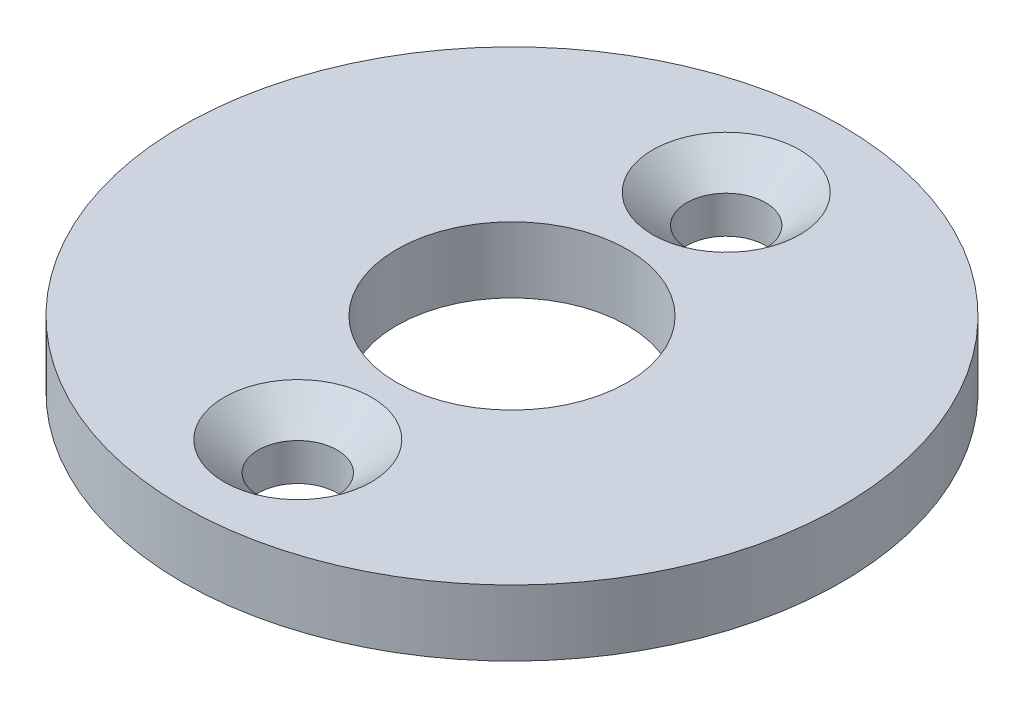
SolidWorks part; units mm, degrees
material "6061-T6 (SS)"
ref_plane "Front Plane" through (0, 0, 0) normal (0, 0, 1) x (1, 0, 0)
ref_plane "Top Plane" through (0, 0, 0) normal (0, 1, 0) x (1, 0, 0)
ref_plane "Right Plane" through (0, 0, 0) normal (1, 0, 0) x (0, 0, -1)
sketch "Sketch1" plane through (0, 0, 0) normal (0, 1, 0) x (1, 0, 0)
  circle A0 centre (0, 0) radius 5.5562
  circle A1 centre (0, 0) radius 15.875
  point P4 (0, 0)
  dimension "D1" = 11.1125
  dimension "D2" = 31.75
extrude "Boss-Extrude1" add sketch "Sketch1" along normal blind 3.175
hole_wizard "CSK for #6 Flat Head Machine Screw (100)1" positions "Sketch4" profile "Sketch2" countersink size "#6" standard "ANSI Inch" end condition through all
sketch "Sketch4" plane through (0, 3.175, 0) normal (0, 1, 0) x (1, 0, 0)
  circle A0 centre (0, 0) radius 10.3187 construction
  point P0 (0, -10.3187)
  point P2 (0, 10.3187)
  dimension "D1" = 20.6375
sketch "Sketch2" plane through (0, 3.175, 10.3187) normal (1, 0, 0) x (0, 0, 1)
  line L0 (0, 0) -> (0, 3.175)
  line L1 (0, 3.175) -> (1.8986, 3.175)
  line L2 (1.8986, 3.175) -> (1.8986, 1.38)
  line L3 (1.8986, 1.38) -> (3.5433, 0)
  line L5 (3.5433, 0) -> (0, 0)
  line L6 (-1.8986, 1.38) -> (-3.5433, 0) construction
  line L11 (0, -6.35) -> (0, 107.95) construction
  dimension "Thru Hole Dia." = 3.7973
  dimension "Thru Hole Depth" = 3.175
  dimension "Near C'Sink Dia." = 7.0866
  dimension "Near C'Sink Angle" = 100
